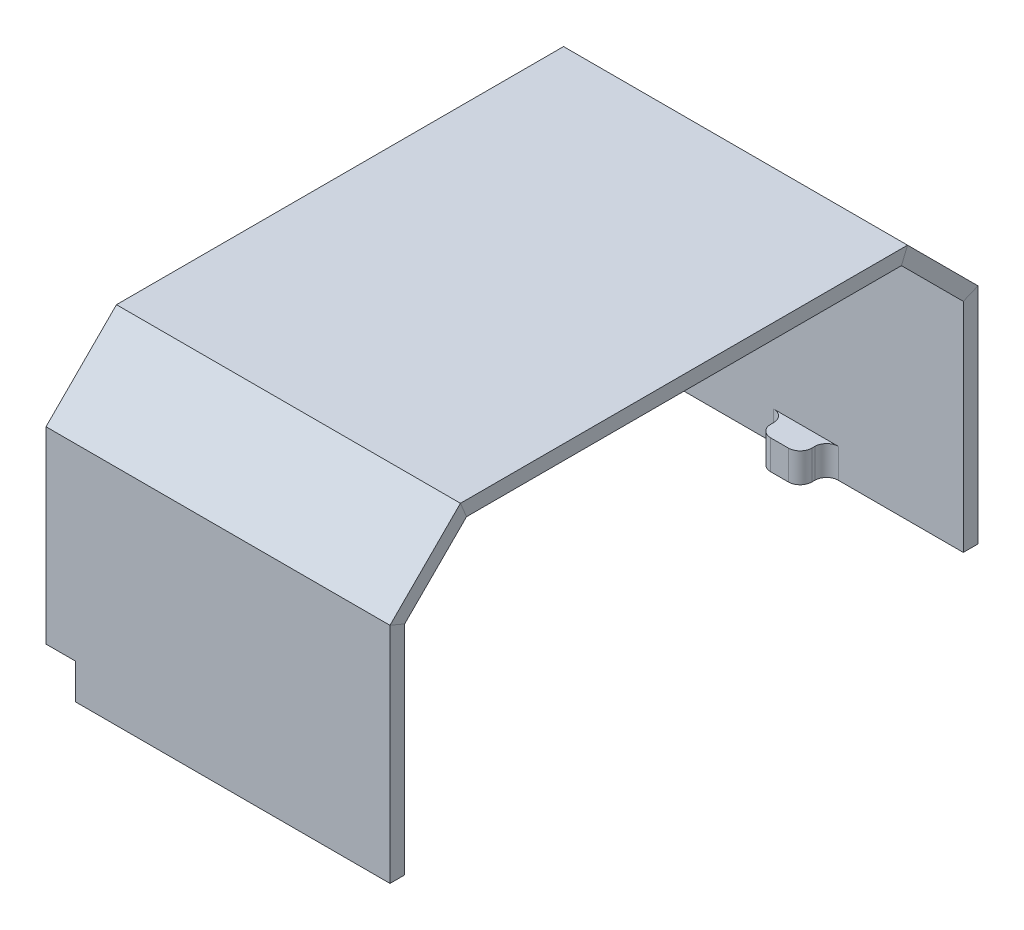
SolidWorks part; units mm, degrees
ref_plane "Front Plane" through (0, 0, 0) normal (0, 0, 1) x (1, 0, 0)
ref_plane "Top Plane" through (0, 0, 0) normal (0, 1, 0) x (1, 0, 0)
ref_plane "Right Plane" through (0, 0, 0) normal (1, 0, 0) x (0, 0, -1)
sketch "Sketch1" plane through (0, 0, 0) normal (0, 1, 0) x (1, 0, 0)
  line L1 (-50, -95) -> (50, -95)
  line L2 (-50, -95) -> (-50, -100)
  line L3 (-50, -100) -> (50, -100)
  line L4 (50, -95) -> (50, -100)
  line L5 (-50, -95) -> (50, -100) construction
  line L6 (-50, -100) -> (50, -95) construction
  line L7 (-50, 100) -> (50, 100) construction
  line L8 (-50, 100) -> (-50, 95) construction
  line L9 (-50, 95) -> (50, 95) construction
  line L10 (50, 100) -> (50, 95) construction
  line L11 (-50, 100) -> (50, 95) construction
  line L12 (-50, 95) -> (50, 100) construction
  point P4 (0, -97.5)
  point P9 (0, 97.5)
  dimension "D1" = 200
  dimension "D2" = 5
  dimension "D3" = 5
  dimension "D4" = 100
  dimension "D5" = 100
  dimension "D6" = 100
  dimension "D7" = 50
  dimension "D8" = 50
sketch "Sketch2" plane through (0, 0, 0) normal (1, 0, 0) x (0, 0, -1)
  line L0 (-97.5, 0) -> (-97.5, 75)
  line L1 (97.5, 0) -> (97.5, 75)
  line L2 (100, 0) -> (95, 0) construction
  line L3 (75, 97.5) -> (-75, 97.5)
  line L4 (-97.5, 75) -> (-75, 97.5)
  line L5 (75, 97.5) -> (97.5, 75)
  point P1 (0, 97.5)
  dimension "D1" = 150
  dimension "D2" = 0
  dimension "D3" = 97.5
  dimension "D4" = 0
sweep "Sweep3" add profiles "Sketch1" path "Sketch2"
ref_plane "Plane1" through (20, 0, 0) normal (1, 0, 0) x (0, 0, -1)
sketch "Sketch3" plane through (20, 0, 0) normal (1, 0, 0) x (0, 0, -1)
  line L1 (-100, 76.0355) -> (-76.0355, 100)
  line L2 (-76.0355, 100) -> (76.0355, 100)
  line L3 (76.0355, 100) -> (100, 76.0355)
  line L7 (95, 73.9645) -> (73.9645, 95)
  line L8 (73.9645, 95) -> (-73.9645, 95)
  line L9 (-73.9645, 95) -> (-95, 73.9645)
  line L12 (-100, 76.0355) -> (-95, 73.9645)
  line L13 (95, 73.9645) -> (100, 76.0355)
sketch "Sketch4" plane through (0, 100, 0) normal (0, 1, 0) x (1, 0, 0)
  point P0 (30.439, 28.6485)
sketch "Sketch5" plane through (-50, 0, 0) normal (-1, 0, 0) x (0, 0, 1)
  line L0 (-100, 0) -> (-95, 0)
  line L1 (-95, 0) -> (-95, 73.9645)
  line L2 (-95, 73.9645) -> (-73.9645, 95)
  line L3 (-73.9645, 95) -> (73.9645, 95)
  line L4 (73.9645, 95) -> (95, 73.9645)
  line L5 (95, 73.9645) -> (95, 0)
  line L6 (95, 0) -> (100, 0)
  line L7 (100, 0) -> (100, 76.0355)
  line L8 (100, 76.0355) -> (76.0355, 100)
  line L9 (76.0355, 100) -> (-76.0355, 100)
  line L10 (-76.0355, 100) -> (-100, 76.0355)
  line L11 (-100, 76.0355) -> (-100, 0)
extrude "Boss-Extrude1" add sketch "Sketch5" along normal blind 17
sketch "Sketch6" plane through (0, 0, -100) normal (0, 0, -1) x (-1, 0, 0)
  line L0 (57, 0) -> (57, 12)
  line L1 (67, 0) -> (-50, 0) construction
  line L2 (57, 12) -> (67, 12)
  line L3 (67, 76.0355) -> (67, 0) construction
  line L4 (67, 12) -> (67, 0)
  line L5 (67, 0) -> (57, 0)
  dimension "D1" = 10
  dimension "D2" = 12
extrude "Cut-Extrude1" cut sketch "Sketch6" against normal through all
sketch "Sketch7" plane through (0, 0, 0) normal (0, -1, 0) x (1, 0, 0)
  line L5 (-57, 100) -> (-57, 95) construction
  line L6 (-10.5, 100) -> (3.5, 100)
  line L10 (-57, 100) -> (50, 100) construction
  line L11 (-10.5, 100) -> (-10.5, 86)
  line L12 (-10.5, 86) -> (3.5, 86)
  line L13 (3.5, 100) -> (3.5, 86)
  line L14 (-10.5, 100) -> (3.5, 86) construction
  line L15 (-10.5, 86) -> (3.5, 100) construction
  point P4 (-3.5, 86)
  point P5 (-3.5, 93)
  dimension "D1" = 14
  dimension "D2" = 14
  dimension "D3" = 53.5
extrude "Boss-Extrude2" add sketch "Sketch7" against normal blind 10
sketch "Sketch8" plane through (0, 0, 0) normal (0, -1, 0) x (1, 0, 0)
  line L0 (-57, 100) -> (50, 100) construction
  line L1 (3.5, 86) -> (3.5, 95) construction
  circle A0 centre (-3.5, 93) radius 6
  dimension "D1" = 12
  dimension "D2" = 7
  dimension "D3" = 7
extrude "Cut-Extrude2" cut sketch "Sketch8" against normal blind 2
fillet "Fillet1" radius 4 4 edges at (3.5, 5, 95) (-10.5, 5, 95) (-10.5, 5, 86) (3.5, 5, 86)
sketch "Sketch9" plane through (0, 0, 0) normal (0, -1, 0) x (1, 0, 0)
  line L0 (-57, -100) -> (50, -100) construction
  line L1 (-10.5, -100) -> (3.5, -100)
  line L2 (-10.5, -100) -> (-10.5, -86)
  line L3 (-10.5, -86) -> (3.5, -86)
  line L4 (3.5, -100) -> (3.5, -86)
  line L5 (-10.5, -100) -> (3.5, -86) construction
  line L6 (-10.5, -86) -> (3.5, -100) construction
  line L7 (-57, -95) -> (-57, -100) construction
  point P4 (-3.5, -93)
  dimension "D1" = 14
  dimension "D2" = 14
  dimension "D3" = 53.5
extrude "Boss-Extrude3" add sketch "Sketch9" against normal blind 10
sketch "Sketch10" plane through (0, 0, 0) normal (0, -1, 0) x (1, 0, 0)
  line L0 (-57, -100) -> (50, -100) construction
  line L1 (-10.5, -86) -> (-10.5, -95) construction
  circle A0 centre (-3.5, -93) radius 6
  dimension "D1" = 12
  dimension "D2" = 7
  dimension "D3" = 7
extrude "Cut-Extrude3" cut sketch "Sketch10" against normal blind 2
fillet "Fillet2" radius 4 4 edges at (-10.5, 5, -95) (-10.5, 5, -86) (3.5, 5, -86) (3.5, 5, -95)
